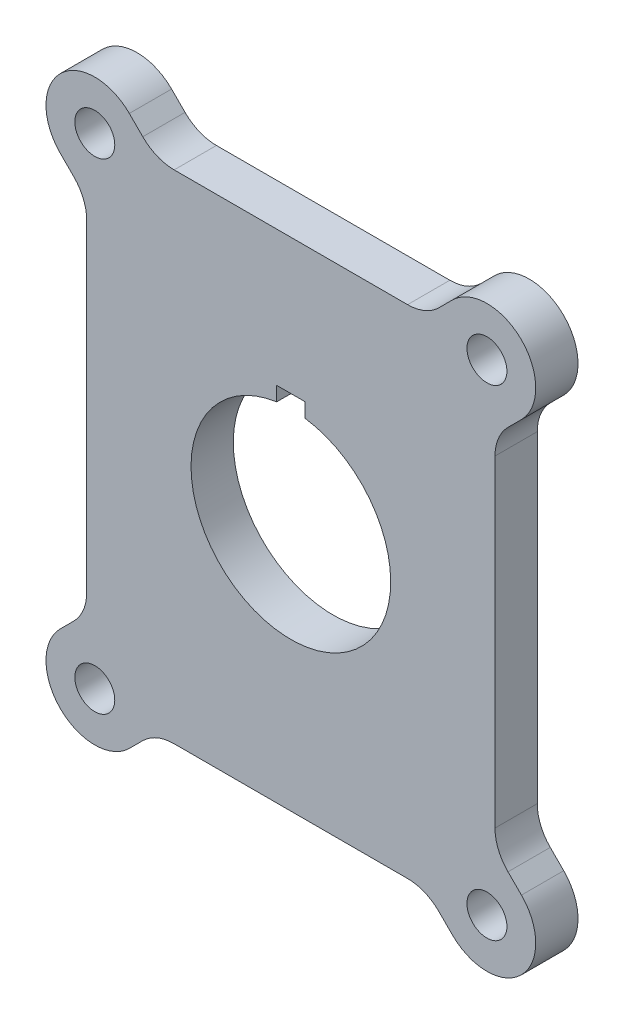
SolidWorks part; units mm, degrees
material "Acrylic (Medium-high impact)"
ref_plane "X-Y Datum" through (0, 0, 0) normal (0, 0, 1) x (1, 0, 0)
ref_plane "X-Z Datum" through (0, 0, 0) normal (0, 1, 0) x (1, 0, 0)
ref_plane "Y-Z Datum" through (0, 0, 0) normal (1, 0, 0) x (0, 0, -1)
sketch "Sketch4" plane through (0, 0, -59.6689) normal (0, 0, 1) x (1, 0, 0)
  line L0 (-30.7488, 11.711) -> (15.2512, 11.711) construction
  line L1 (-6.1488, 22.8466) -> (-6.1488, 24.461)
  line L2 (-9.3488, 22.8466) -> (-9.3488, 24.461)
  line L3 (-9.3488, 24.461) -> (-6.1488, 24.461)
  line L12 (5.402, 39.711) -> (-20.8995, 39.711)
  line L13 (-24.4351, 41.1754) -> (-25.951, 42.6914)
  line L14 (-33.7292, 34.9132) -> (-32.2132, 33.3973)
  line L15 (-30.7488, 29.8617) -> (-30.7488, -6.4398)
  line L16 (-32.2132, -9.9753) -> (-33.7292, -11.4913)
  line L17 (-25.951, -19.2695) -> (-24.4351, -17.7535)
  line L18 (-20.8995, -16.289) -> (5.402, -16.289)
  line L19 (8.9375, -17.7535) -> (10.4535, -19.2695)
  line L20 (18.2317, -11.4913) -> (16.7157, -9.9753)
  line L22 (16.7157, 33.3973) -> (18.2317, 34.9132)
  line L23 (10.4535, 42.6914) -> (8.9375, 41.1754)
  line L24 (5.402, 39.711) -> (-20.8995, 39.711)
  line L25 (-24.4351, 41.1754) -> (-25.951, 42.6914)
  line L26 (-33.7292, 34.9132) -> (-32.2132, 33.3973)
  line L28 (-32.2132, -9.9753) -> (-33.7292, -11.4913)
  line L29 (-25.951, -19.2695) -> (-24.4351, -17.7535)
  line L30 (-20.8995, -16.289) -> (5.402, -16.289)
  line L31 (8.9375, -17.7535) -> (10.4535, -19.2695)
  line L32 (18.2317, -11.4913) -> (16.7157, -9.9753)
  line L34 (16.7157, 33.3973) -> (18.2317, 34.9132)
  line L35 (10.4535, 42.6914) -> (8.9375, 41.1754)
  line L43 (-30.7488, 29.8617) -> (-30.7488, -6.4398)
  line L45 (15.2512, -6.4398) -> (15.2512, 29.8617)
  line L47 (15.2512, -6.4398) -> (15.2512, 29.8617)
  arc A1 (-9.3488, 22.8466) -> (-6.1488, 22.8466) centre (-7.7488, 11.711) ccw
  arc A4 (-25.951, 42.6914) -> (-33.7292, 34.9132) centre (-29.8401, 38.8023) ccw
  arc A5 (-33.7292, -11.4913) -> (-25.951, -19.2695) centre (-29.8401, -15.3804) ccw
  arc A6 (10.4535, -19.2695) -> (18.2317, -11.4913) centre (14.3426, -15.3804) ccw
  arc A7 (18.2317, 34.9132) -> (10.4535, 42.6914) centre (14.3426, 38.8023) ccw
  arc A8 (-25.951, 42.6914) -> (-33.7292, 34.9132) centre (-29.8401, 38.8023) ccw
  arc A9 (-33.7292, -11.4913) -> (-25.951, -19.2695) centre (-29.8401, -15.3804) ccw
  arc A10 (10.4535, -19.2695) -> (18.2317, -11.4913) centre (14.3426, -15.3804) ccw
  arc A11 (18.2317, 34.9132) -> (10.4535, 42.6914) centre (14.3426, 38.8023) ccw
  arc A34 (5.402, 39.711) -> (8.9375, 41.1754) centre (5.402, 44.711) ccw
  arc A35 (5.402, 39.711) -> (8.9375, 41.1754) centre (5.402, 44.711) ccw
  arc A36 (-24.4351, 41.1754) -> (-20.8995, 39.711) centre (-20.8995, 44.711) ccw
  arc A37 (-24.4351, 41.1754) -> (-20.8995, 39.711) centre (-20.8995, 44.711) ccw
  arc A38 (-30.7488, 29.8617) -> (-32.2132, 33.3973) centre (-35.7488, 29.8617) ccw
  arc A39 (-30.7488, 29.8617) -> (-32.2132, 33.3973) centre (-35.7488, 29.8617) ccw
  arc A40 (-32.2132, -9.9753) -> (-30.7488, -6.4398) centre (-35.7488, -6.4398) ccw
  arc A41 (-32.2132, -9.9753) -> (-30.7488, -6.4398) centre (-35.7488, -6.4398) ccw
  arc A42 (-20.8995, -16.289) -> (-24.4351, -17.7535) centre (-20.8995, -21.289) ccw
  arc A43 (-20.8995, -16.289) -> (-24.4351, -17.7535) centre (-20.8995, -21.289) ccw
  arc A44 (8.9375, -17.7535) -> (5.402, -16.289) centre (5.402, -21.289) ccw
  arc A45 (8.9375, -17.7535) -> (5.402, -16.289) centre (5.402, -21.289) ccw
  arc A46 (15.2512, -6.4398) -> (16.7157, -9.9753) centre (20.2512, -6.4398) ccw
  arc A47 (15.2512, -6.4398) -> (16.7157, -9.9753) centre (20.2512, -6.4398) ccw
  arc A48 (16.7157, 33.3973) -> (15.2512, 29.8617) centre (20.2512, 29.8617) ccw
  arc A49 (16.7157, 33.3973) -> (15.2512, 29.8617) centre (20.2512, 29.8617) ccw
  point P11 (0, 0)
  point P14 (-7.7488, 11.711)
  point P29 (-7.7488, 24.461)
  dimension "D2" = 22.5
  dimension "D3" = 3.2
  dimension "D4" = 1.6144
  dimension "D1" = 0
extrude "Boss-Extrude1" add sketch "Sketch4" along normal blind 4.7625
hole_wizard "M4 Clearance Hole2" positions "Sketch5" profile "Sketch6" hole size "M4" standard "ANSI Metric" end condition through all
sketch "Sketch5" plane through (0, 0, -54.9064) normal (0, 0, 1) x (1, 0, 0)
  point P0 (-29.8401, 38.8023)
  point P3 (14.3426, 38.8023)
  point P6 (14.3426, -15.3804)
  point P9 (-29.8401, -15.3804)
sketch "Sketch6" plane through (-29.8401, 38.8023, -54.9064) normal (1, 0, 0) x (0, -1, 0)
  line L0 (0, 0) -> (0, 4.7625)
  line L1 (0, 4.7625) -> (2.25, 4.7625)
  line L2 (2.25, 4.7625) -> (2.25, 0)
  line L5 (2.25, 0) -> (0, 0)
  line L11 (0, -6.35) -> (0, 107.95) construction
  dimension "Thru Hole Dia." = 4.5
  dimension "Thru Hole Depth" = 4.7625
